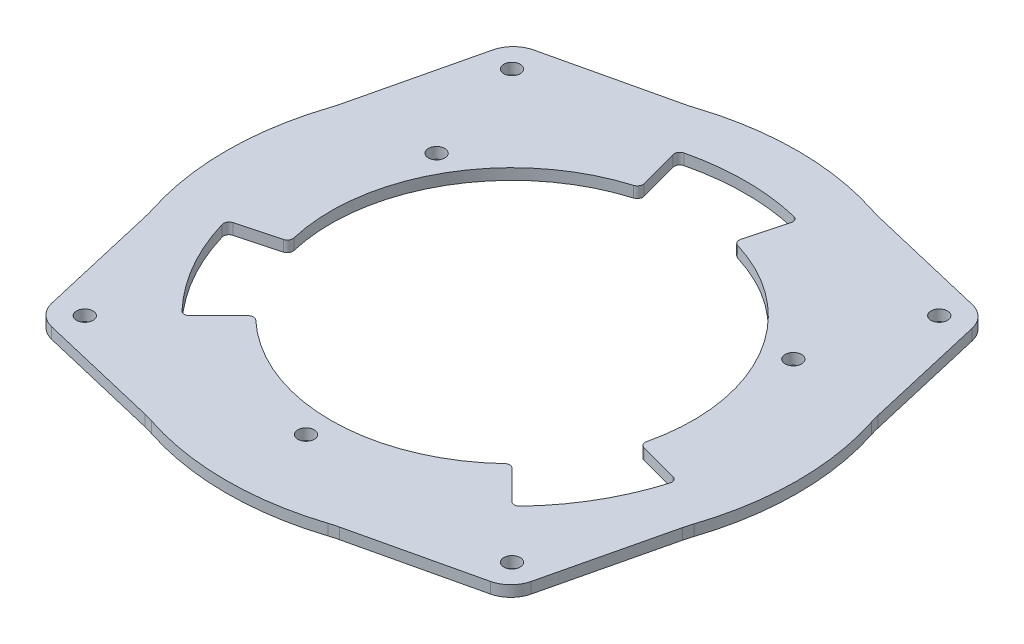
SolidWorks part; units mm, degrees
material "6061-T6 (SS)"
ref_plane "Front Plane" through (0, 0, 0) normal (0, 0, 1) x (1, 0, 0)
ref_plane "Top Plane" through (0, 0, 0) normal (0, 1, 0) x (1, 0, 0)
ref_plane "Right Plane" through (0, 0, 0) normal (1, 0, 0) x (0, 0, -1)
sketch "Sketch1" plane through (0, 0, 0) normal (0, 1, 0) x (1, 0, 0)
  line L0 (49.872, -261.8935) -> (473.872, -261.8935) construction
  line L1 (17.8971, 48.9297) -> (40.1493, 43.6512)
  line L2 (43.8664, 39.9141) -> (49.0252, 17.6338)
  line L3 (48.9297, -17.8971) -> (43.6512, -40.1493)
  line L4 (39.9141, -43.8664) -> (17.6338, -49.0252)
  line L5 (-17.8971, -48.9297) -> (-40.1493, -43.6512)
  line L6 (-43.8664, -39.9141) -> (-49.0252, -17.6338)
  line L7 (-48.9297, 17.8971) -> (-43.6512, 40.1493)
  line L8 (-39.9141, 43.8664) -> (-17.6338, 49.0252)
  line L9 (0, 38.8907) -> (0, -38.8907) construction
  line L10 (-38.8907, 0) -> (38.8907, 0) construction
  line L11 (-32.476, 18.75) -> (0, -37.5) construction
  line L12 (-38.8907, 38.8907) -> (38.8907, 38.8907) construction
  line L13 (-38.8907, 38.8907) -> (-38.8907, -38.8907) construction
  line L14 (-38.8907, -38.8907) -> (38.8907, -38.8907) construction
  line L15 (38.8907, 38.8907) -> (38.8907, -38.8907) construction
  line L16 (0, -37.5) -> (32.476, 18.75) construction
  line L17 (32.476, 18.75) -> (-32.476, 18.75) construction
  line L18 (-32.476, 18.75) -> (16.238, -9.375) construction
  line L19 (0, -37.5) -> (0, 18.75) construction
  circle A0 centre (0, 0) radius 30 construction
  arc A1 (-17.6338, 49.0252) -> (-15.9939, 49.4792) centre (-22.1454, 68.5097) ccw
  arc A2 (0.1397, 51.9998) -> (-15.9939, 49.4792) centre (0, 0) ccw
  arc A3 (16.2596, 49.3926) -> (0.1397, 51.9998) centre (0, 0) ccw
  arc A4 (16.2596, 49.3926) -> (17.8971, 48.9297) centre (22.5132, 68.3897) ccw
  arc A5 (43.8664, 39.9141) -> (40.1493, 43.6512) centre (38.9952, 38.7862) ccw
  arc A6 (49.0252, 17.6338) -> (49.4792, 15.9939) centre (68.5097, 22.1454) ccw
  arc A7 (49.3926, -16.2596) -> (49.4792, 15.9939) centre (0, 0) ccw
  arc A8 (49.3926, -16.2596) -> (48.9297, -17.8971) centre (68.3897, -22.5132) ccw
  arc A9 (39.9141, -43.8664) -> (43.6512, -40.1493) centre (38.7862, -38.9952) ccw
  arc A10 (17.6338, -49.0252) -> (15.9939, -49.4792) centre (22.1454, -68.5097) ccw
  arc A11 (-16.2596, -49.3926) -> (15.9939, -49.4792) centre (0, 0) ccw
  arc A12 (-16.2596, -49.3926) -> (-17.8971, -48.9297) centre (-22.5132, -68.3897) ccw
  arc A13 (-43.8664, -39.9141) -> (-40.1493, -43.6512) centre (-38.9952, -38.7862) ccw
  arc A14 (-49.0252, -17.6338) -> (-49.4792, -15.9939) centre (-68.5097, -22.1454) ccw
  arc A15 (-49.3926, 16.2596) -> (-49.4792, -15.9939) centre (0, 0) ccw
  arc A16 (-49.3926, 16.2596) -> (-48.9297, 17.8971) centre (-68.3897, 22.5132) ccw
  arc A17 (-39.9141, 43.8664) -> (-43.6512, 40.1493) centre (-38.7862, 38.9952) ccw
  circle A18 centre (-38.8907, 38.8907) radius 1.5
  circle A19 centre (38.8907, 38.8907) radius 1.5
  circle A20 centre (38.8907, -38.8907) radius 1.5
  circle A21 centre (-38.8907, -38.8907) radius 1.5
  circle A22 centre (0, 0) radius 33
  circle A23 centre (-32.476, 18.75) radius 1.5
  circle A24 centre (0, -37.5) radius 1.5
  circle A25 centre (32.476, 18.75) radius 1.5
  point P22 (0, 0)
  point P65 (0, 0)
  point P66 (0, 0)
  point P69 (0, 0)
  point P70 (0, 0)
  dimension "D1" = 3
  dimension "D2" = 60
  dimension "D3" = 66
  dimension "D4" = 3
  dimension "D5" = 37.5
extrude "Boss-Extrude1" add sketch "Sketch1" along normal blind 2
sketch "Sketch2" plane through (0, 2, 0) normal (0, 1, 0) x (1, 0, 0)
  line L0 (0, 0) -> (0, 42.5) construction
  line L1 (0, 0) -> (-36.8061, -21.25) construction
  line L2 (0, 0) -> (36.8061, -21.25) construction
  line L3 (-8.541, 31.8756) -> (-10.9998, 41.0518)
  line L4 (8.541, 31.8756) -> (10.9998, 41.0518)
  line L5 (-31.8756, -8.541) -> (-41.0518, -10.9998)
  line L6 (-23.3345, -23.3345) -> (-30.052, -30.052)
  line L7 (23.3345, -23.3345) -> (30.052, -30.052)
  line L8 (31.8756, -8.541) -> (41.0518, -10.9998)
  circle A0 centre (0, 0) radius 33 construction
  arc A1 (8.541, 31.8756) -> (-8.541, 31.8756) centre (0, 0) ccw
  arc A2 (-41.0518, -10.9998) -> (-30.052, -30.052) centre (0, 0) ccw
  arc A3 (-31.8756, -8.541) -> (-23.3345, -23.3345) centre (0, 0) ccw
  arc A4 (10.9998, 41.0518) -> (-10.9998, 41.0518) centre (0, 0) ccw
  arc A5 (30.052, -30.052) -> (41.0518, -10.9998) centre (0, 0) ccw
  arc A6 (23.3345, -23.3345) -> (31.8756, -8.541) centre (0, 0) ccw
  dimension "D3" = 85
  dimension "D1" = 120
  dimension "D2" = 120
  dimension "D4" = 15
  dimension "D5" = 15
  dimension "D6" = 15
  dimension "D7" = 15
  dimension "D8" = 15
  dimension "D9" = 15
extrude "Cut-Extrude1" cut sketch "Sketch2" against normal through all
fillet "Fillet1" radius 1 12 edges at (-31.8756, 1, 8.541) (-41.0518, 1, 10.9998) (-30.052, 1, 30.052) (-23.3345, 1, 23.3345) (23.3345, 1, 23.3345) (30.052, 1, 30.052) (41.0518, 1, 10.9998) (31.8756, 1, 8.541) (8.541, 1, -31.8756) (10.9998, 1, -41.0518) (-10.9998, 1, -41.0518) (-8.541, 1, -31.8756)
